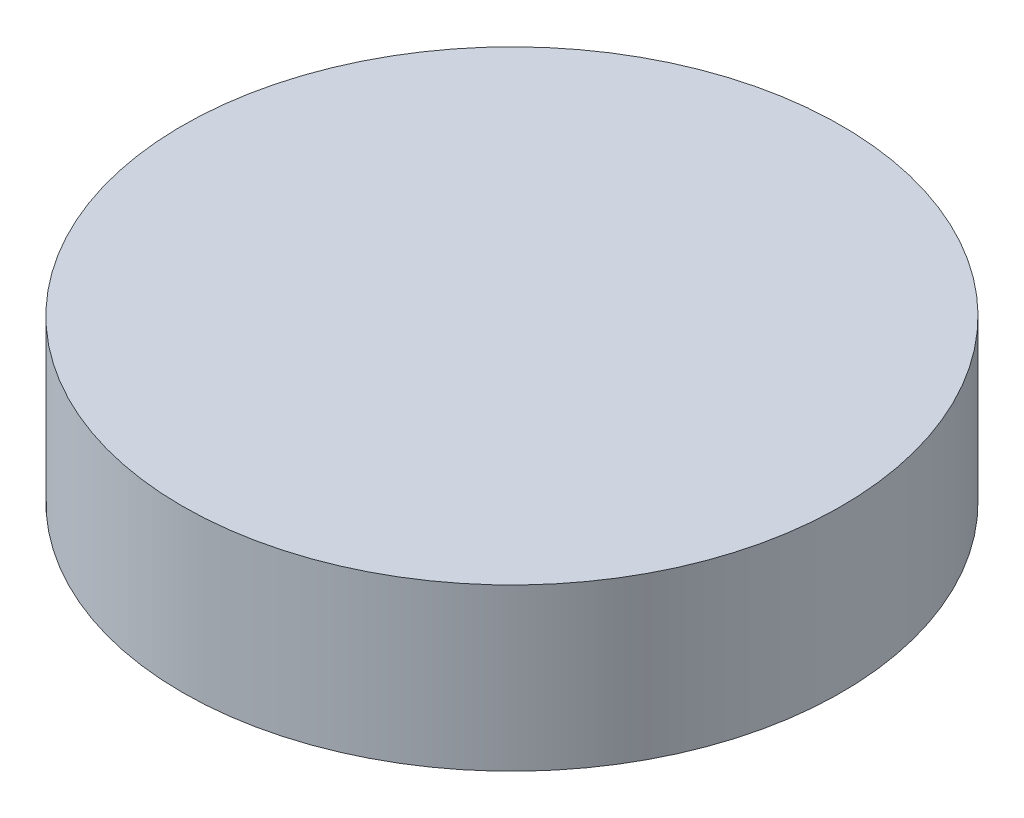
SolidWorks part; units mm, degrees
ref_plane "Front Plane" through (0, 0, 0) normal (0, 0, 1) x (1, 0, 0)
ref_plane "Top Plane" through (0, 0, 0) normal (0, 1, 0) x (1, 0, 0)
ref_plane "Right Plane" through (0, 0, 0) normal (1, 0, 0) x (0, 0, -1)
sketch "Sketch1" plane through (0, 0, 0) normal (0, 1, 0) x (1, 0, 0)
  circle A0 centre (0, 0) radius 38
  dimension "D1" = 76
extrude "Boss-Extrude1" add sketch "Sketch1" along normal blind 18.6
